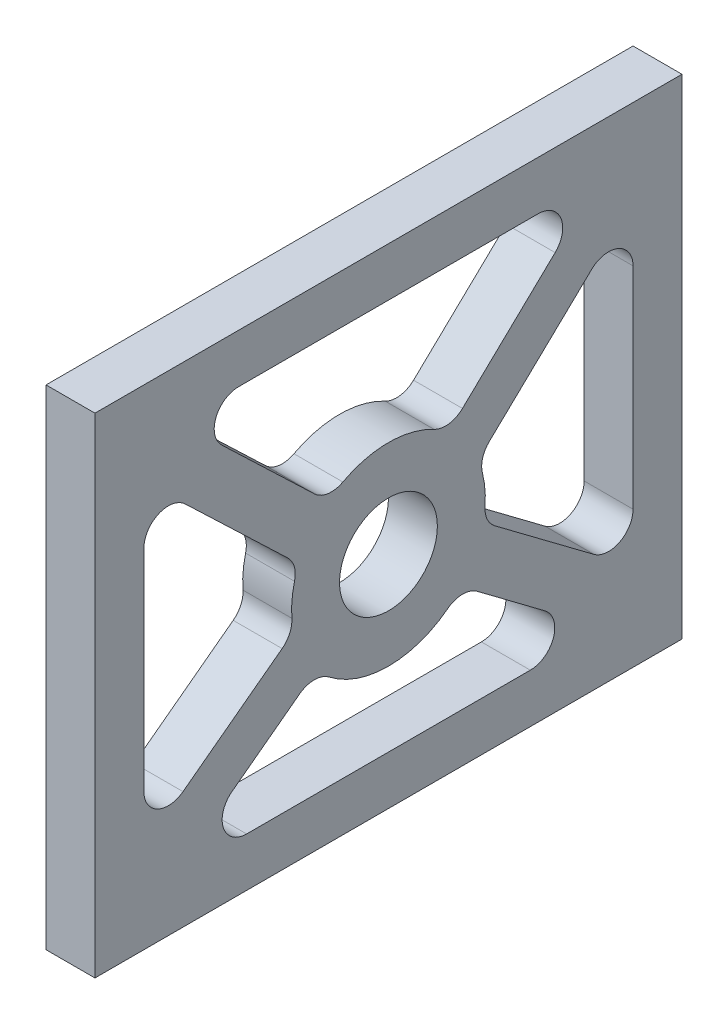
SolidWorks part; units mm, degrees
ref_plane "Front Plane" through (0, 0, 0) normal (0, 0, 1) x (1, 0, 0)
ref_plane "Top Plane" through (0, 0, 0) normal (0, 1, 0) x (1, 0, 0)
ref_plane "Right Plane" through (0, 0, 0) normal (1, 0, 0) x (0, 0, -1)
sketch "Sketch1" plane through (0, 0, 0) normal (1, 0, 0) x (0, 0, -1)
  line L0 (0, -28.575) -> (0, 34.925) construction
  line L1 (-38.1, 34.925) -> (38.1, 34.925)
  line L2 (-38.1, 34.925) -> (-38.1, -28.575)
  line L3 (-38.1, -28.575) -> (38.1, -28.575)
  line L4 (38.1, 34.925) -> (38.1, -28.575)
  circle A0 centre (0, 0) radius 6.35
  point P5 (0, 0)
  point P9 (0, 0)
  point P11 (0, 0)
  dimension "D3" = 12.7
  dimension "D1" = 76.2
  dimension "D2" = 63.5
  dimension "D4" = 28.575
extrude "Boss-Extrude1" add sketch "Sketch1" along normal blind 6.35
sketch "Sketch4" plane through (6.35, 0, 0) normal (1, 0, 0) x (0, 0, -1)
  line L0 (-9.4155, -8.3361) -> (-27.9409, -22.225)
  line L1 (-27.9409, -22.225) -> (27.9409, -22.225)
  line L2 (-12.3101, -2.5698) -> (-31.75, -17.1443)
  line L3 (-31.75, -17.1443) -> (-31.75, 23.9848)
  line L4 (-31.75, 23.9848) -> (-11.6393, 4.7612)
  line L5 (-27.3623, 28.575) -> (-7.7934, 9.8694)
  line L6 (-27.3623, 28.575) -> (27.3623, 28.575)
  line L7 (0, 28.575) -> (0, -22.225) construction
  line L8 (-38.1, -28.575) -> (38.1, -28.575) construction
  line L9 (-38.1, 34.925) -> (-38.1, -28.575) construction
  line L10 (38.1, 34.925) -> (-38.1, 34.925) construction
  line L11 (-31.75, -17.1443) -> (-27.9409, -22.225) construction
  line L12 (-31.75, 23.9848) -> (-27.3623, 28.575) construction
  line L13 (31.75, 23.9848) -> (11.6393, 4.7612)
  line L14 (12.3101, -2.5698) -> (31.75, -17.1443)
  line L15 (31.75, -17.1443) -> (31.75, 23.9848)
  line L16 (9.4155, -8.3361) -> (27.9409, -22.225)
  line L17 (27.3623, 28.575) -> (7.7934, 9.8694)
  arc A0 (7.7934, 9.8694) -> (-7.7934, 9.8694) centre (0, 0) ccw
  arc A1 (-11.6393, 4.7612) -> (-12.3101, -2.5698) centre (0, 0) ccw
  arc A2 (-9.4155, -8.3361) -> (9.4155, -8.3361) centre (0, 0) ccw
  arc A3 (11.6393, 4.7612) -> (12.3101, -2.5698) centre (0, 0) cw
  point P12 (-29.5532, 28.575)
  point P20 (-31.75, -19.6784)
  dimension "D1" = 6.35
  dimension "D2" = 6.35
  dimension "D3" = 6.35
  dimension "D4" = 6.35
  dimension "D5" = 6.35
extrude "Cut-Extrude1" cut sketch "Sketch4" against normal up to next
fillet "Fillet2" radius 3.175 16 edges at (3.175, -22.225, -27.9409) (3.175, -17.1443, -31.75) (3.175, 23.9848, -31.75) (3.175, 28.575, -27.3623) (3.175, 28.575, 27.3623) (3.175, 23.9848, 31.75) (3.175, -17.1443, 31.75) (3.175, -22.225, 27.9409) (3.175, 4.7612, 11.6393) (3.175, -2.5698, 12.3101) (3.175, -8.3361, 9.4155) (3.175, -8.3361, -9.4155) (3.175, -2.5698, -12.3101) (3.175, 4.7612, -11.6393) (3.175, 9.8694, -7.7934) (3.175, 9.8694, 7.7934)
